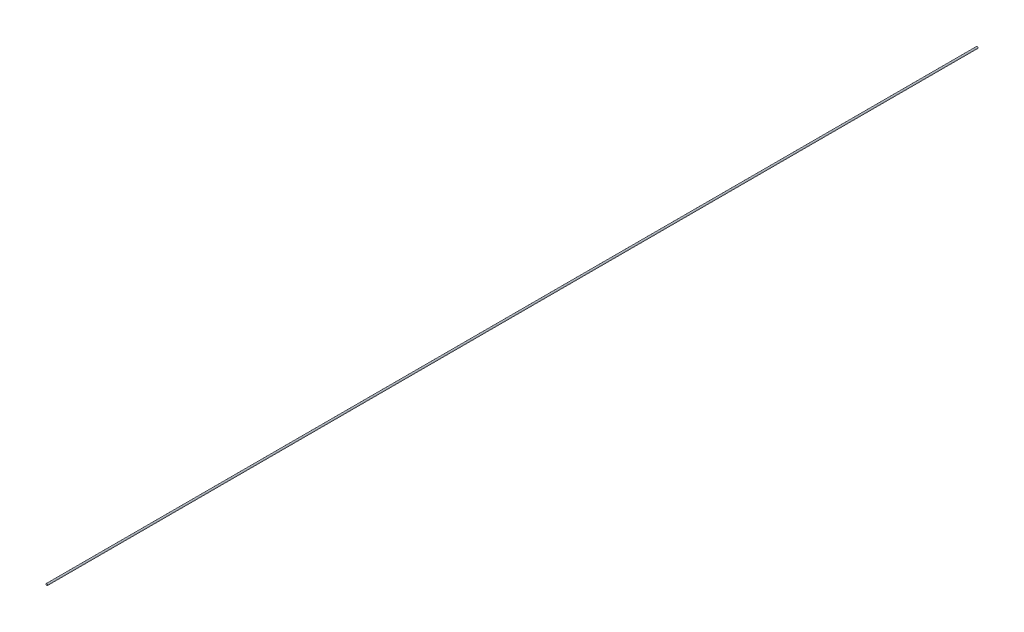
SolidWorks part; units mm, degrees
material "AISI 1015 Aço, trefilado (SS)"
ref_plane "Plano frontal" through (0, 0, 0) normal (0, 0, 1) x (1, 0, 0)
ref_plane "Plano superior" through (0, 0, 0) normal (0, 1, 0) x (1, 0, 0)
ref_plane "Plano direito" through (0, 0, 0) normal (1, 0, 0) x (0, 0, -1)
sketch "Esboço1" plane through (0, 0, 0) normal (0, 0, 1) x (1, 0, 0)
  circle A0 centre (0, 0) radius 3
  dimension "D1" = 6
extrude "Ressalto-extrusão1" add sketch "Esboço1" along normal mid plane 3300 contours A0
